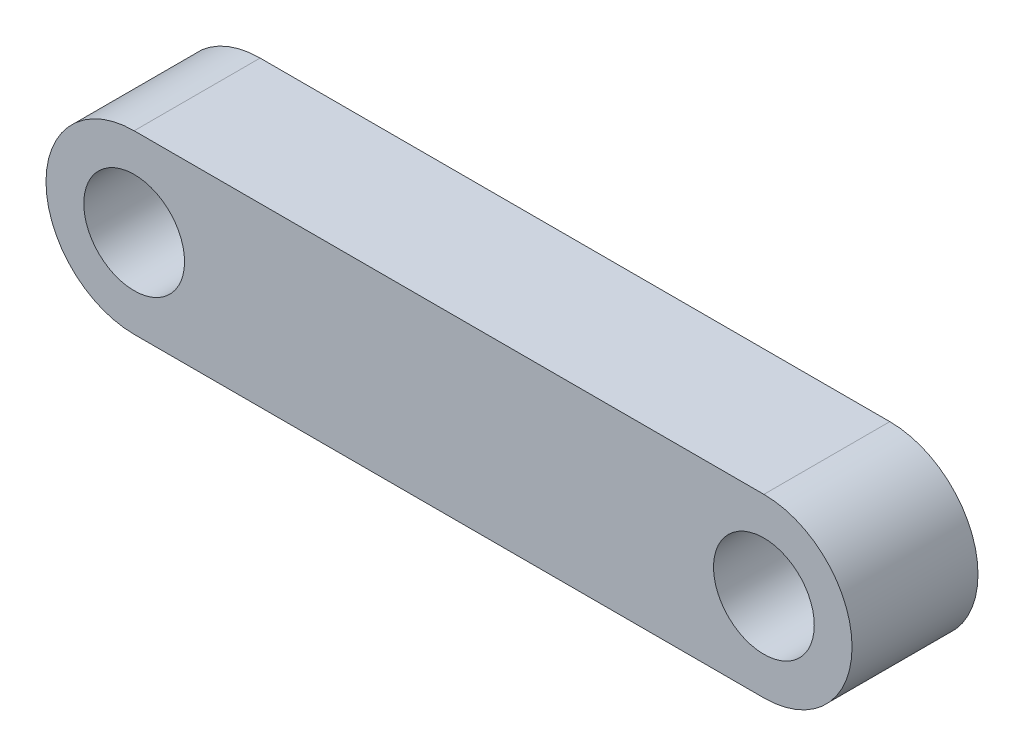
SolidWorks part; units mm, degrees
ref_plane "Plan de face" through (0, 0, 0) normal (0, 0, 1) x (1, 0, 0)
ref_plane "Plan de dessus" through (0, 0, 0) normal (0, 1, 0) x (1, 0, 0)
ref_plane "Plan de droite" through (0, 0, 0) normal (1, 0, 0) x (0, 0, -1)
sketch "Sketch1" plane through (0, 0, 0) normal (0, 0, 1) x (1, 0, 0)
  line L1 (-12.5, -3.5) -> (12.5, -3.5)
  line L2 (-12.5, -3.5) -> (-12.5, 3.5)
  line L3 (-12.5, 3.5) -> (12.5, 3.5)
  line L4 (12.5, -3.5) -> (12.5, 3.5)
  line L5 (-12.5, -3.5) -> (12.5, 3.5) construction
  line L6 (-12.5, 3.5) -> (12.5, -3.5) construction
  circle A0 centre (-12.5, 0) radius 3.5
  circle A1 centre (12.5, 0) radius 3.5
  circle A2 centre (-12.5, 0) radius 2
  circle A3 centre (12.5, 0) radius 2
  point P0 (0, 0)
  dimension "D3" = 4
  dimension "D4" = 4
  dimension "D1" = 25
  dimension "D2" = 7
extrude "Boss-Extrude1" add sketch "Sketch1" along normal blind 5 contours A1 L3 A0 L1 | A3 L4 A1 | A3 L4 A1 | A2
